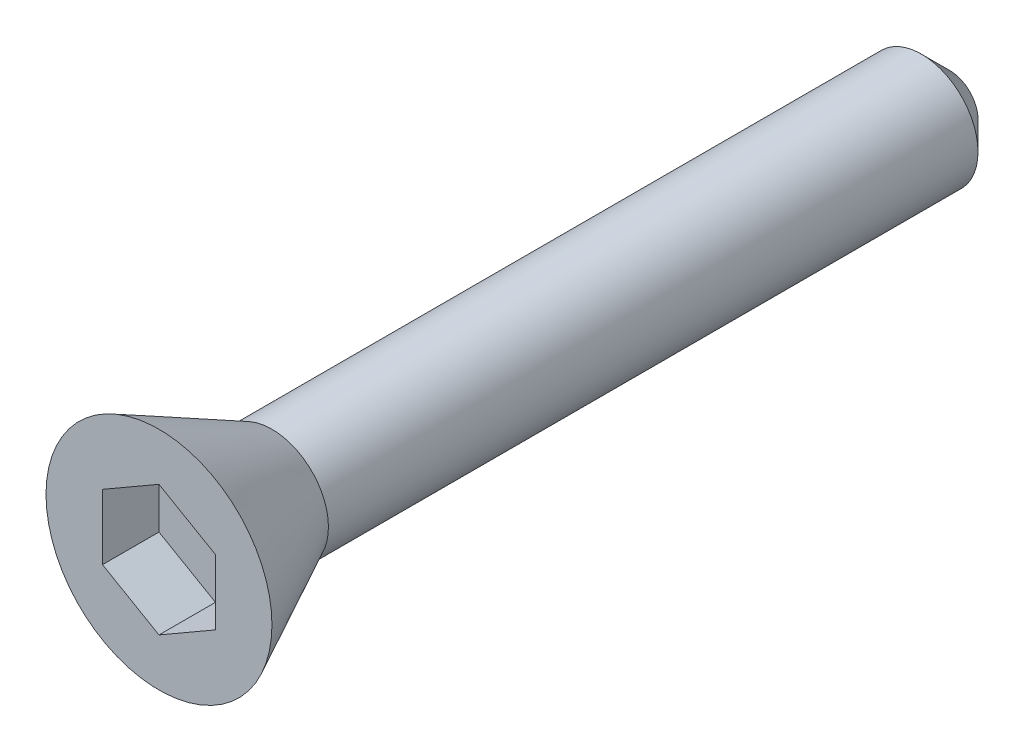
SolidWorks part; units mm, degrees
ref_plane "Front Plane" through (0, 0, 0) normal (0, 0, 1) x (1, 0, 0)
ref_plane "Top Plane" through (0, 0, 0) normal (0, 1, 0) x (1, 0, 0)
ref_plane "Right Plane" through (0, 0, 0) normal (1, 0, 0) x (0, 0, -1)
sketch "Sketch1" plane through (0, 0, 0) normal (1, 0, 0) x (0, 0, -1)
  line L0 (-58.5147, 0) -> (2867.2225, 0) construction
  line L1 (0, 0) -> (0, 2)
  line L2 (0, 2) -> (2, 1)
  line L3 (2, 1) -> (14, 1)
  line L4 (14, 1) -> (14, 0)
  line L5 (14, 0) -> (0, 0)
  dimension "D1" = 2
  dimension "D2" = 4
  dimension "D3" = 12
  dimension "D4" = 2
revolve "Body" add sketch "Sketch1" angle 360 about L0
sketch "Sketch2" plane through (0, 0, 0) normal (0, 0, 1) x (1, 0, 0)
  line L1 (0, 1.1547) -> (-1, 0.5774)
  line L2 (-1, 0.5774) -> (-1, -0.5774)
  line L3 (-1, -0.5774) -> (0, -1.1547)
  line L4 (0, -1.1547) -> (1, -0.5774)
  line L5 (1, -0.5774) -> (1, 0.5774)
  line L6 (1, 0.5774) -> (0, 1.1547)
  circle A0 centre (0, 0) radius 1 construction
  dimension "D1" = 2
extrude "Footprint" cut sketch "Sketch2" against normal blind 1
chamfer "Chamfer1" distance 0.5 angle 45 1 edges at (1, 0, -14)
